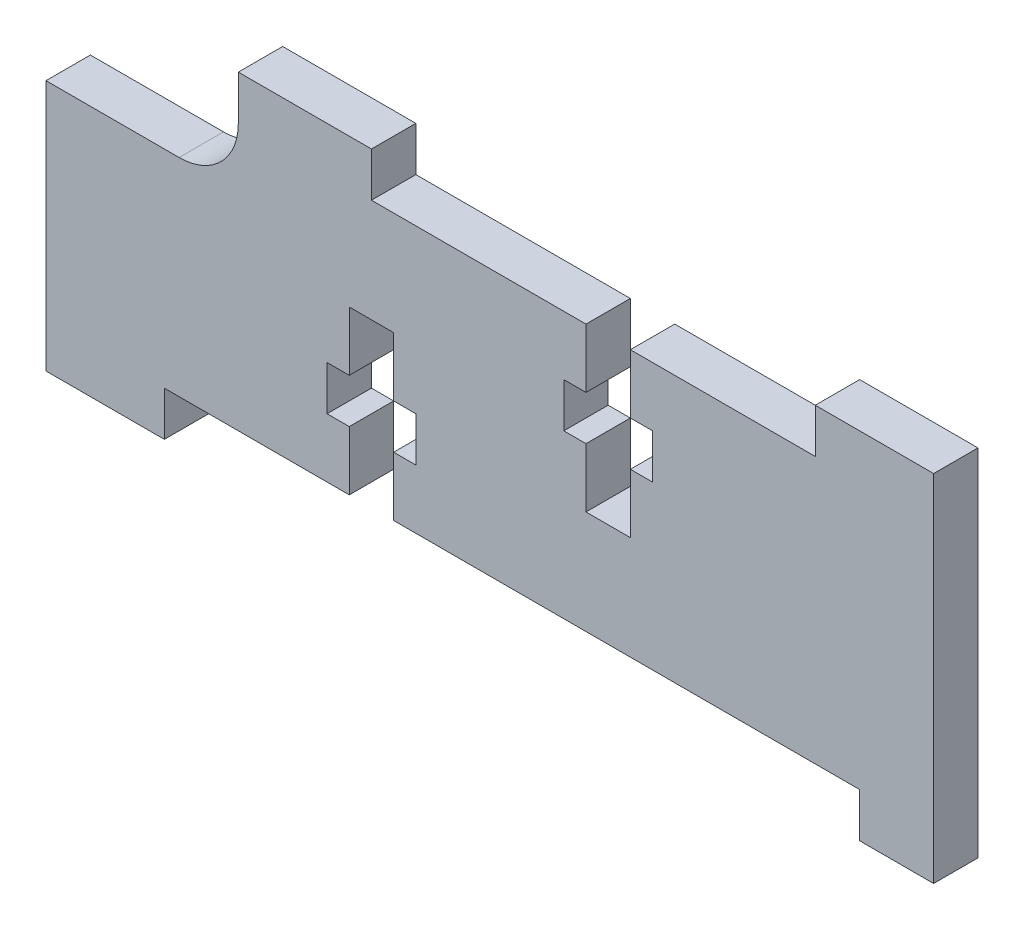
SolidWorks part; units mm, degrees
ref_plane "Plan de face" through (0, 0, 0) normal (0, 0, 1) x (1, 0, 0)
ref_plane "Plan de dessus" through (0, 0, 0) normal (0, 1, 0) x (1, 0, 0)
ref_plane "Plan de droite" through (0, 0, 0) normal (1, 0, 0) x (0, 0, -1)
sketch "Esquisse5" plane through (0, 0, 0) normal (0, 0, 1) x (1, 0, 0)
  line L0 (-17.1404, 14.4466) -> (-17.1404, 17.4466)
  line L1 (-14.1404, -3.5534) -> (-45.6404, -3.5534)
  line L2 (-14.1404, -3.5534) -> (-14.1404, -6.5534)
  line L3 (-17.1404, 14.4466) -> (-29.6404, 14.4466)
  line L4 (-61.1404, -3.5534) -> (-61.1404, -6.5534)
  line L5 (-17.1404, 17.4466) -> (-9.1404, 17.4466)
  line L6 (-14.1404, -6.5534) -> (-9.1404, -6.5534)
  line L7 (-9.1404, 17.4466) -> (-9.1404, -6.5534)
  line L8 (-61.1404, -6.5534) -> (-69.1404, -6.5534)
  line L9 (-69.1404, -6.5534) -> (-69.1404, 10.4466)
  line L10 (-47.1404, 14.4466) -> (-47.1404, 17.4466)
  line L11 (-47.1404, 17.4466) -> (-56.1404, 17.4466)
  line L12 (-56.1404, 17.4466) -> (-56.1404, 14.4466)
  line L13 (-60.1404, 10.4466) -> (-69.1404, 10.4466)
  line L14 (-32.6404, 14.4466) -> (-47.1404, 14.4466)
  line L15 (-48.6404, 3.4466) -> (-48.6404, 7.4466)
  line L16 (-45.6404, -3.5534) -> (-45.6404, 0.4466)
  line L17 (-45.6404, 7.4466) -> (-48.6404, 7.4466)
  line L18 (-48.6404, -3.5534) -> (-48.6404, 0.4466)
  line L19 (-48.6404, -3.5534) -> (-61.1404, -3.5534)
  line L20 (-29.6404, 14.4466) -> (-29.6404, 10.4466)
  line L21 (-29.6404, 3.4466) -> (-32.6404, 3.4466)
  line L22 (-32.6404, 14.4466) -> (-32.6404, 10.4466)
  line L23 (-50.1404, 3.4466) -> (-48.6404, 3.4466)
  line L24 (-50.1404, 3.4466) -> (-50.1404, 0.4466)
  line L25 (-50.1404, 0.4466) -> (-48.6404, 0.4466)
  line L26 (-44.1404, 3.4466) -> (-44.1404, 0.4466)
  line L27 (-34.1404, 10.4466) -> (-32.6404, 10.4466)
  line L28 (-34.1404, 10.4466) -> (-34.1404, 7.4466)
  line L29 (-34.1404, 7.4466) -> (-32.6404, 7.4466)
  line L30 (-28.1404, 10.4466) -> (-28.1404, 7.4466)
  line L31 (-45.6404, 3.4466) -> (-44.1404, 3.4466)
  line L32 (-45.6404, 3.4466) -> (-45.6404, 7.4466)
  line L33 (-45.6404, 0.4466) -> (-44.1404, 0.4466)
  line L34 (-29.6404, 10.4466) -> (-28.1404, 10.4466)
  line L35 (-32.6404, 7.4466) -> (-32.6404, 3.4466)
  line L36 (-29.6404, 7.4466) -> (-28.1404, 7.4466)
  line L37 (-29.6404, 7.4466) -> (-29.6404, 3.4466)
  arc A0 (-56.1404, 14.4466) -> (-60.1404, 10.4466) centre (-60.1404, 14.4466) cw
  dimension "D9" = 4
  dimension "D1" = 18
  dimension "D2" = 8
  dimension "D3" = 3
  dimension "D4" = 3
  dimension "D5" = 3
  dimension "D6" = 8
  dimension "D7" = 9
  dimension "D8" = 3
  dimension "D10" = 17
  dimension "D11" = 60
  dimension "D12" = 47
  dimension "D13" = 3
  dimension "D14" = 3
  dimension "D15" = 11
  dimension "D16" = 11
  dimension "D17" = 3
  dimension "D18" = 3
  dimension "D19" = 1.5
  dimension "D20" = 1.5
  dimension "D21" = 1.5
  dimension "D22" = 1.5
  dimension "D23" = 12.5
  dimension "D24" = 30
  dimension "D25" = 12.5
extrude "Boss.-Extru.5" add sketch "Esquisse5" along normal blind 3 separate body
